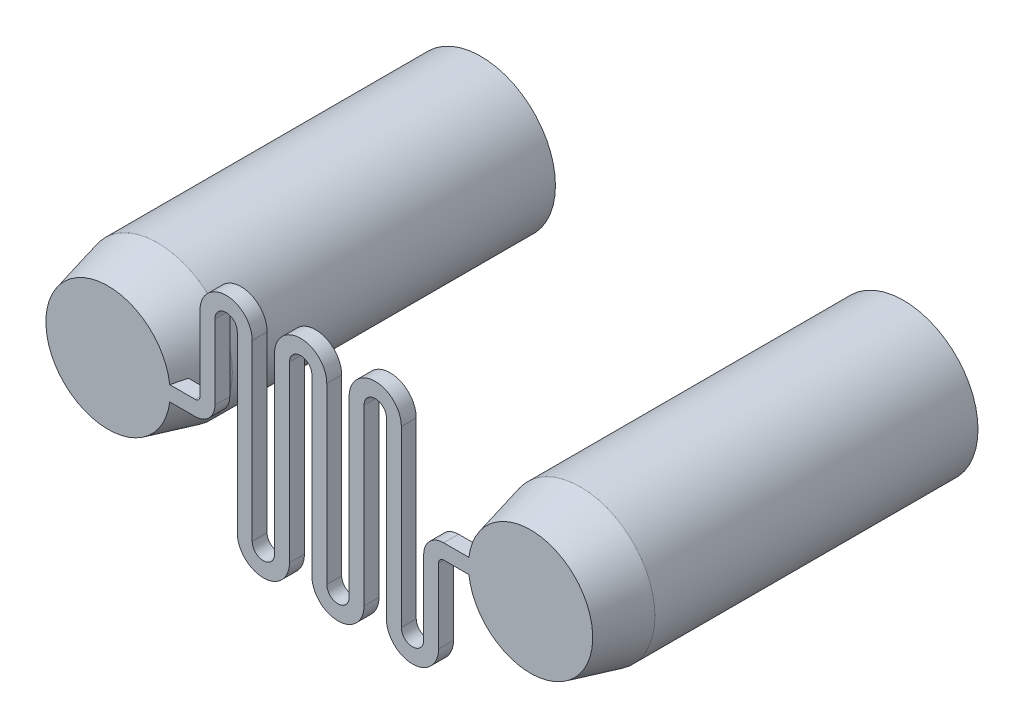
SolidWorks part; units mm, degrees
ref_plane "Front Plane" through (0, 0, 0) normal (0, 0, 1) x (1, 0, 0)
ref_plane "Top Plane" through (0, 0, 0) normal (0, 1, 0) x (1, 0, 0)
ref_plane "Right Plane" through (0, 0, 0) normal (1, 0, 0) x (0, 0, -1)
sketch "Sketch2" plane through (0, 0, 0) normal (0, 0, 1) x (1, 0, 0)
  line L3 (-20.5, -0.6) -> (-13.5, -0.6)
  line L6 (-11.9, 1) -> (-11.9, 7)
  line L9 (-10.1, 7) -> (-10.1, 0)
  line L12 (-10.1, 0) -> (-10.1, -7)
  line L15 (-5.9, -7) -> (-5.9, 0)
  line L18 (-5.9, 0) -> (-5.9, 7)
  line L21 (-4.1, 7) -> (-4.1, 0)
  line L22 (-4.1, 0) -> (-4.1, -7)
  line L23 (0.1, -7) -> (0.1, 0)
  line L24 (0.1, 0) -> (0.1, 7)
  line L25 (1.9, 7) -> (1.9, 0)
  line L26 (1.9, 0) -> (1.9, -7)
  line L27 (6.1, -7) -> (6.1, -1)
  line L28 (6.5, -0.6) -> (13.5, -0.6)
  line L29 (-20.5, 0.6) -> (-13.5, 0.6)
  line L30 (-13.1, 1) -> (-13.1, 7)
  line L31 (-8.9, 7) -> (-8.9, 0)
  line L32 (-8.9, 0) -> (-8.9, -7)
  line L33 (-7.1, -7) -> (-7.1, 0)
  line L34 (-7.1, 0) -> (-7.1, 7)
  line L35 (-2.9, 7) -> (-2.9, 0)
  line L36 (-2.9, 0) -> (-2.9, -7)
  line L37 (-1.1, -7) -> (-1.1, 0)
  line L38 (-1.1, 0) -> (-1.1, 7)
  line L39 (3.1, 7) -> (3.1, 0)
  line L40 (3.1, 0) -> (3.1, -7)
  line L41 (4.9, -7) -> (4.9, -1)
  line L42 (6.5, 0.6) -> (13.5, 0.6)
  arc A0 (-20.5, 0.6) -> (-20.5, -0.6) centre (-20.5, 0) ccw
  arc A1 (13.5, -0.6) -> (13.5, 0.6) centre (13.5, 0) ccw
  arc A8 (-11.9, 1) -> (-13.5, -0.6) centre (-13.5, 1) cw
  arc A9 (-11.9, 7) -> (-10.1, 7) centre (-11, 7) cw
  arc A10 (-10.1, -7) -> (-5.9, -7) centre (-8, -7) ccw
  arc A11 (-5.9, 7) -> (-4.1, 7) centre (-5, 7) cw
  arc A12 (-4.1, -7) -> (0.1, -7) centre (-2, -7) ccw
  arc A13 (0.1, 7) -> (1.9, 7) centre (1, 7) cw
  arc A14 (1.9, -7) -> (6.1, -7) centre (4, -7) ccw
  arc A15 (6.1, -1) -> (6.5, -0.6) centre (6.5, -1) cw
  arc A16 (-13.1, 1) -> (-13.5, 0.6) centre (-13.5, 1) cw
  arc A17 (-13.1, 7) -> (-8.9, 7) centre (-11, 7) cw
  arc A18 (-8.9, -7) -> (-7.1, -7) centre (-8, -7) ccw
  arc A19 (-7.1, 7) -> (-2.9, 7) centre (-5, 7) cw
  arc A20 (-2.9, -7) -> (-1.1, -7) centre (-2, -7) ccw
  arc A21 (-1.1, 7) -> (3.1, 7) centre (1, 7) cw
  arc A22 (3.1, -7) -> (4.9, -7) centre (4, -7) ccw
  arc A23 (4.9, -1) -> (6.5, 0.6) centre (6.5, -1) cw
  point P4 (0, 0)
  point P32 (5.5, 0)
  point P35 (-12.5, 0)
  dimension "D1" = 8
extrude "Boss-Extrude1" add sketch "Sketch2" along normal blind 1.2
ref_plane "Plane1" through (0, 0, 0) normal (0, 1, 0) x (1, 0, 0)
sketch "Sketch3" plane through (0, 0, 0) normal (0, 1, 0) x (1, 0, 0)
  line L0 (-20.5, -1.2) -> (-25.5, -1.2)
  line L2 (-20.5, -1.2) -> (-20.5, 28.8)
  line L3 (-20.5, 28.8) -> (-26.5, 28.8)
  line L4 (-26.5, 28.8) -> (-26.5, 2.8)
  line L5 (-26.5, 2.8) -> (-25.5, -1.2)
  dimension "D1" = 5
  dimension "D3" = 30
  dimension "D4" = 6
revolve "Revolve1" add sketch "Sketch3" angle 360 about L2
ref_plane "Plane2" through (0, 0, 0) normal (0, 1, 0) x (1, 0, 0)
sketch "Sketch4" plane through (0, 0, 0) normal (0, 1, 0) x (1, 0, 0)
  line L0 (13.5, -1.2) -> (18.5, -1.2)
  line L2 (13.5, -1.2) -> (13.5, 28.8)
  line L3 (13.5, 28.8) -> (19.5, 28.8)
  line L4 (19.5, 28.8) -> (19.5, 2.8)
  line L5 (19.5, 2.8) -> (18.5, -1.2)
  dimension "D1" = 5
  dimension "D3" = 30
  dimension "D4" = 6
revolve "Revolve2" add sketch "Sketch4" angle 360 about L2
sketch "Sketch5" plane through (0, 0, -28.8) normal (0, 0, -1) x (-1, 0, 0)
  circle A0 centre (20.5, 0) radius 5
  circle A1 centre (-13.5, 0) radius 5
  dimension "D1" = 10
  dimension "D2" = 10
extrude "Cut-Extrude1" cut sketch "Sketch5" against normal blind 28
